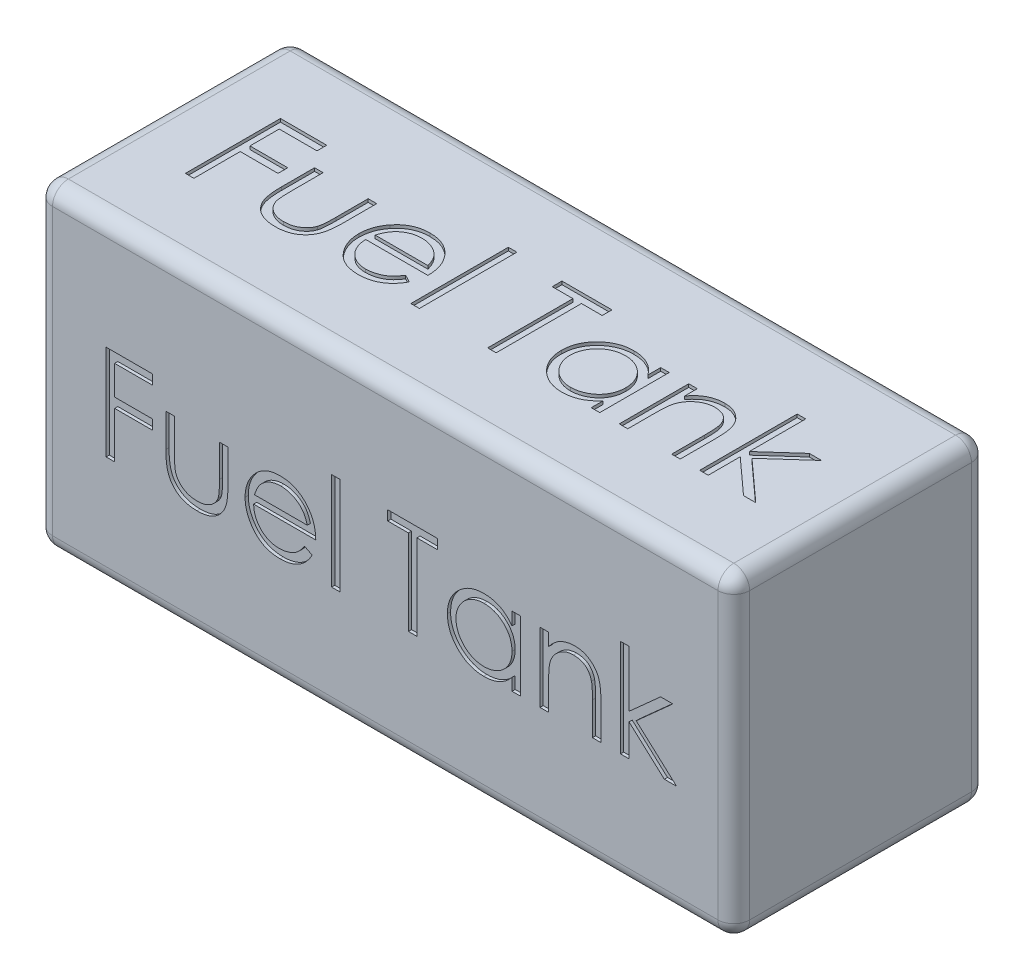
SolidWorks part; units mm, degrees
ref_plane "Front Plane" through (0, 0, 0) normal (0, 0, 1) x (1, 0, 0)
ref_plane "Top Plane" through (0, 0, 0) normal (0, 1, 0) x (1, 0, 0)
ref_plane "Right Plane" through (0, 0, 0) normal (1, 0, 0) x (0, 0, -1)
sketch "Sketch2" plane through (0, 0, 0) normal (0, 1, 0) x (1, 0, 0)
  line L1 (-110, 40) -> (110, 40)
  line L2 (-110, 40) -> (-110, -40)
  line L3 (-110, -40) -> (110, -40)
  line L4 (110, 40) -> (110, -40)
  line L5 (-110, 40) -> (110, -40) construction
  line L6 (-110, -40) -> (110, 40) construction
  point P0 (0, 0)
  dimension "D1" = 220
  dimension "D2" = 80
extrude "Boss-Extrude1" add sketch "Sketch2" along normal mid plane 100
sketch "Sketch3" plane through (0, 50, 0) normal (0, 1, 0) x (1, 0, 0)
  line L0 (-110, 0) -> (110, 0) construction
  line L1 (-110, 40) -> (-110, -40) construction
  line L2 (110, -40) -> (110, 40) construction
  line L3 (-110, 15) -> (110, 15) construction
  line L4 (-110, -15) -> (110, -15) construction
  line L5 (-89.3295, 15) -> (-89.3295, 0) construction
  line L6 (-89.3295, 0) -> (-89.3295, -15) construction
  text T0 "Fuel Tank" font "Century Gothic" height 30
  dimension "D1" = 30
extrude "Cut-Extrude1" cut sketch "Sketch3" against normal blind 1
sketch "Sketch4" plane through (0, 0, -40) normal (0, 0, -1) x (-1, 0, 0)
  line L0 (-110, 0) -> (110, 0) construction
  line L1 (-110, 50) -> (-110, -50) construction
  line L2 (110, 50) -> (110, -50) construction
  line L3 (-110, -15) -> (110, -15) construction
  line L4 (-110, 15) -> (110, 15) construction
  text T0 "Fuel Tank" font "Century Gothic" height 30
  dimension "D1" = 30
extrude "Cut-Extrude2" cut sketch "Sketch4" against normal blind 1
sketch "Sketch5" plane through (0, 0, 40) normal (0, 0, 1) x (1, 0, 0)
  line L0 (-110, 0) -> (110, 0) construction
  line L1 (-110, 50) -> (-110, -50) construction
  line L2 (110, 50) -> (110, -50) construction
  line L3 (-110, -15) -> (110, -15) construction
  line L4 (-110, 15) -> (110, 15) construction
  text T0 "Fuel Tank" font "Century Gothic" height 30
  dimension "D1" = 30
extrude "Cut-Extrude3" cut sketch "Sketch5" against normal blind 1
fillet "Fillet1" radius 5 12 edges at (-110, 0, 40) (-110, -50, 0) (0, -50, -40) (110, -50, 0) (0, -50, 40) (-110, 0, -40) (110, 0, 40) (110, 0, -40) (-110, 50, 0) (0, 50, 40) (110, 50, 0) (0, 50, -40)
